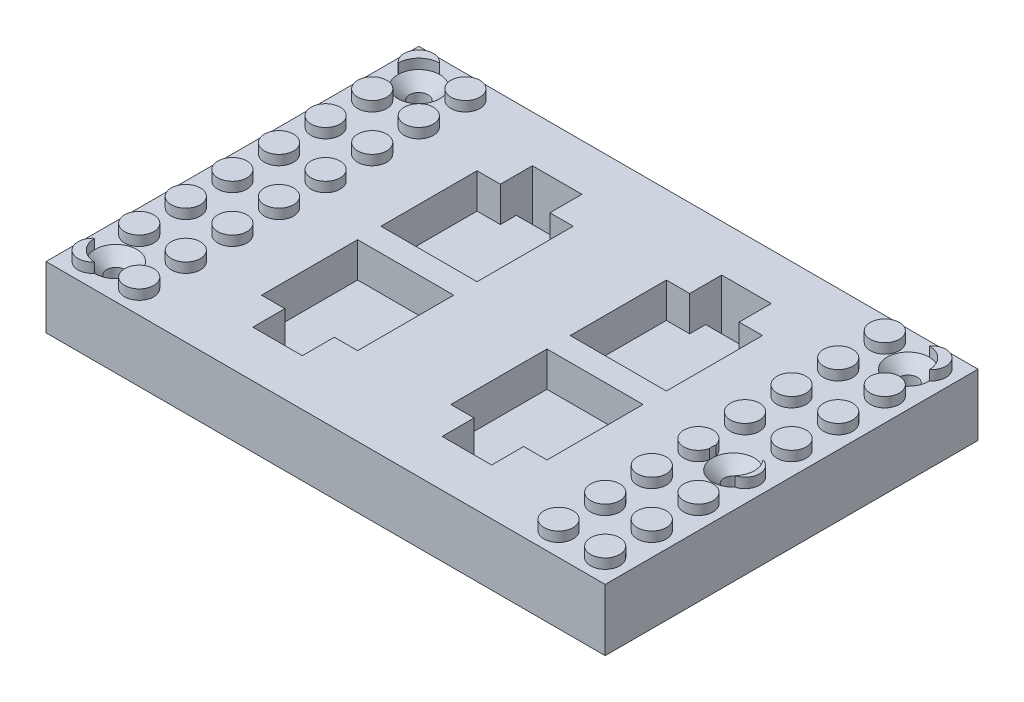
SolidWorks part; units mm, degrees
ref_plane "Front Plane" through (0, 0, 0) normal (0, 0, 1) x (1, 0, 0)
ref_plane "Top Plane" through (0, 0, 0) normal (0, 1, 0) x (1, 0, 0)
ref_plane "Right Plane" through (0, 0, 0) normal (1, 0, 0) x (0, 0, -1)
sketch "Sketch1" plane through (0, 0, 0) normal (0, 1, 0) x (1, 0, 0)
  line L1 (48, 32) -> (-48, 32)
  line L2 (48, 32) -> (48, -32)
  line L3 (48, -32) -> (-48, -32)
  line L4 (-48, 32) -> (-48, -32)
  line L5 (48, 32) -> (-48, -32) construction
  line L6 (48, -32) -> (-48, 32) construction
  point P0 (0, 0)
  dimension "D1" = 96
  dimension "D2" = 64
extrude "Boss-Extrude1" add sketch "Sketch1" along normal blind 10.6
sketch "Sketch2" plane through (0, 10.6, 0) normal (0, 1, 0) x (1, 0, 0)
  line L0 (-20.5, 18.5) -> (-20.5, 24)
  line L1 (-24.5, 2) -> (-8, 2)
  line L2 (-24.5, 2) -> (-24.5, 18.5)
  line L3 (-24.5, 18.5) -> (-20.5, 18.5)
  line L4 (-8, 2) -> (-8, 18.5)
  line L5 (-20.5, 24) -> (-12, 24)
  line L6 (-12, 24) -> (-12, 18.5)
  line L7 (-12, 18.5) -> (-8, 18.5)
  line L8 (0, 0) -> (-31.4081, 0) construction
  line L9 (-24.5, -2) -> (-8, -2)
  line L10 (-8, -2) -> (-8, -18.5)
  line L11 (-12, -18.5) -> (-8, -18.5)
  line L12 (-12, -24) -> (-12, -18.5)
  line L13 (-20.5, -24) -> (-12, -24)
  line L14 (-20.5, -18.5) -> (-20.5, -24)
  line L15 (-24.5, -18.5) -> (-20.5, -18.5)
  line L16 (-24.5, -2) -> (-24.5, -18.5)
  line L17 (0, 0) -> (0, 13.7417) construction
  line L18 (24.5, -2) -> (24.5, -18.5)
  line L19 (24.5, -18.5) -> (20.5, -18.5)
  line L20 (20.5, -18.5) -> (20.5, -24)
  line L21 (20.5, -24) -> (12, -24)
  line L22 (12, -24) -> (12, -18.5)
  line L23 (12, -18.5) -> (8, -18.5)
  line L24 (8, -2) -> (8, -18.5)
  line L25 (24.5, -2) -> (8, -2)
  line L26 (24.5, 2) -> (8, 2)
  line L27 (8, 2) -> (8, 18.5)
  line L28 (12, 18.5) -> (8, 18.5)
  line L29 (12, 24) -> (12, 18.5)
  line L30 (20.5, 24) -> (12, 24)
  line L31 (20.5, 18.5) -> (20.5, 24)
  line L32 (24.5, 18.5) -> (20.5, 18.5)
  line L33 (24.5, 2) -> (24.5, 18.5)
  point P6 (-16.25, 2)
  point P9 (-16.25, 24)
  dimension "D1" = 16.5
  dimension "D2" = 16.5
  dimension "D3" = 22
  dimension "D4" = 8.5
  dimension "D5" = 4
  dimension "D6" = 16
extrude "Cut-Extrude1" cut sketch "Sketch2" against normal blind 6
sketch "Sketch3" plane through (0, 4.6, 0) normal (0, 1, 0) x (1, 0, 0)
  line L0 (-12, 18.5) -> (-12, 24) construction
  line L1 (-20.5, 24) -> (-12, 24)
  line L2 (-20.5, 24) -> (-20.5, 21.25)
  line L3 (-20.5, 21.25) -> (-12, 21.25)
  line L4 (-12, 24) -> (-12, 21.25)
  line L5 (20.5, 18.5) -> (20.5, 24) construction
  line L6 (12, 24) -> (20.5, 24)
  line L7 (12, 24) -> (12, 21.25)
  line L8 (12, 21.25) -> (20.5, 21.25)
  line L9 (20.5, 24) -> (20.5, 21.25)
  line L10 (-20.5, -18.5) -> (-20.5, -24) construction
  line L11 (-20.5, -21.25) -> (-12, -21.25)
  line L12 (-20.5, -21.25) -> (-20.5, -24)
  line L13 (-20.5, -24) -> (-12, -24)
  line L14 (-12, -21.25) -> (-12, -24)
  line L15 (12, -18.5) -> (12, -24) construction
  line L16 (12, -21.25) -> (20.5, -21.25)
  line L17 (12, -21.25) -> (12, -24)
  line L18 (12, -24) -> (20.5, -24)
  line L19 (20.5, -21.25) -> (20.5, -24)
  line L20 (12, -24) -> (20.5, -24) construction
  line L21 (12, -24) -> (20.5, -24) construction
  line L22 (20.5, -24) -> (20.5, -18.5) construction
extrude "Cut-Extrude2" cut sketch "Sketch3" against normal through all
sketch "Sketch4" plane through (0, 10.6, 0) normal (0, 1, 0) x (1, 0, 0)
  line L0 (48, 32) -> (-48, 32) construction
  line L1 (-48, 32) -> (-48, -32) construction
  line L2 (0, 0) -> (17.1402, 0) construction
  line L3 (0, 0) -> (0, 18.863) construction
  circle A0 centre (-42, 26) radius 1.6
  circle A1 centre (42, 26) radius 1.6
  circle A2 centre (-42, -26) radius 1.6
  circle A3 centre (42, -4) radius 1.6
  dimension "D3" = 3.2
  dimension "D1" = 6
  dimension "D2" = 6
  dimension "D4" = 30
extrude "Cut-Extrude3" cut sketch "Sketch4" against normal through all
chamfer "Chamfer1" distance 2 angle 45 4 edges at (42, 10.6, -27.6) (42, 10.6, 5.6) (-42, 10.6, 24.4) (-42, 10.6, -24.4)
sketch "Sketch5" plane through (0, 10.6, 0) normal (0, 1, 0) x (1, 0, 0)
  line L0 (-48, 32) -> (-48, -32) construction
  line L1 (-48, 32) -> (-32, 32) construction
  line L2 (-48, 32) -> (-48, -32) construction
  line L3 (-48, -32) -> (-32, -32) construction
  line L4 (-32, 32) -> (-32, -32) construction
  line L5 (48, -32) -> (48, 32) construction
  line L6 (-44, 28) -> (-36, 28) construction
  line L7 (0, 0) -> (0, 17.2149) construction
  line L8 (-48, -32) -> (48, -32) construction
  circle A0 centre (-44, 28) radius 2.5
  circle A1 centre (-36, 28) radius 2.5
  circle A2 centre (-44, 20) radius 2.5
  circle A3 centre (-36, 20) radius 2.5
  circle A4 centre (-44, 12) radius 2.5
  circle A5 centre (-36, 12) radius 2.5
  circle A6 centre (-44, 4) radius 2.5
  circle A7 centre (-36, 4) radius 2.5
  circle A8 centre (-44, -4) radius 2.5
  circle A9 centre (-36, -4) radius 2.5
  circle A10 centre (36, -4) radius 2.5
  circle A11 centre (44, -4) radius 2.5
  circle A12 centre (44, 4) radius 2.5
  circle A13 centre (36, 4) radius 2.5
  circle A14 centre (36, 12) radius 2.5
  circle A15 centre (44, 12) radius 2.5
  circle A16 centre (44, 20) radius 2.5
  circle A17 centre (36, 20) radius 2.5
  circle A18 centre (36, 28) radius 2.5
  circle A19 centre (44, 28) radius 2.5
  circle A20 centre (-44, -12) radius 2.5
  circle A21 centre (-36, -12) radius 2.5
  circle A22 centre (-44, -20) radius 2.5
  circle A23 centre (-36, -20) radius 2.5
  circle A24 centre (-44, -28) radius 2.5
  circle A25 centre (-36, -28) radius 2.5
  circle A27 centre (36, -28) radius 2.5
  circle A28 centre (36, -20) radius 2.5
  circle A29 centre (36, -12) radius 2.5
  circle A30 centre (44, -12) radius 2.5
  circle A31 centre (44, -20) radius 2.5
  circle A32 centre (44, -28) radius 2.5
  point P6 (-48, 0)
  point P9 (48, 0)
  point P14 (-40, 28)
  point P15 (-40, 32)
  dimension "D4" = 5
  dimension "D1" = 8
  dimension "D2" = 16
  dimension "D3" = 4
  dimension "D5" = 8
  dimension "D6" = 8
extrude "Boss-Extrude3" add sketch "Sketch5" along normal blind 1.7
sketch "Sketch6" plane through (0, 10.6, 0) normal (0, 1, 0) x (1, 0, 0)
  circle A0 centre (-42, 26) radius 3.6
  circle A1 centre (-42, -26) radius 3.6
  circle A2 centre (42, -4) radius 3.6
  circle A3 centre (42, 26) radius 3.6
extrude "Cut-Extrude5" cut sketch "Sketch6" along normal through all
